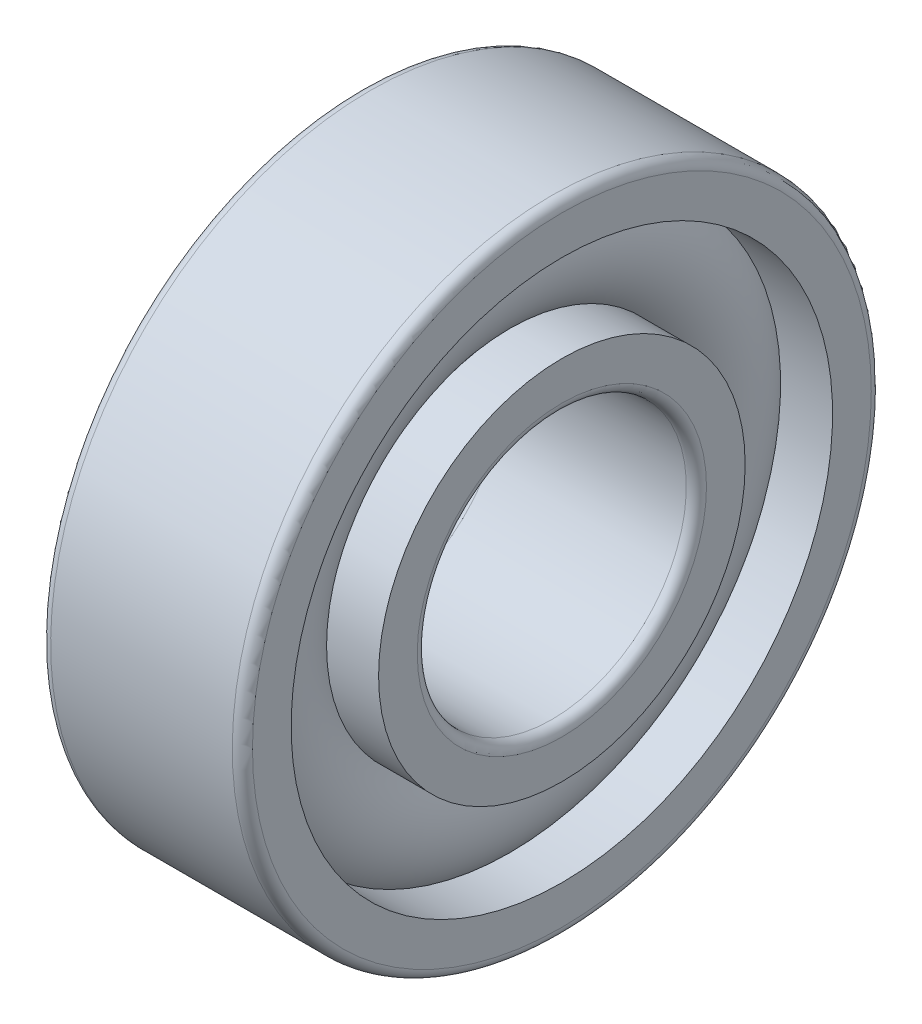
SolidWorks part; units mm, degrees
ref_plane "Plan de face" through (0, 0, 0) normal (0, 0, 1) x (1, 0, 0)
ref_plane "Plan de dessus" through (0, 0, 0) normal (0, 1, 0) x (1, 0, 0)
ref_plane "Plan de droite" through (0, 0, 0) normal (1, 0, 0) x (0, 0, -1)
ref_plane "Plan1" through (0, 0, -411.4604) normal (0, 0, 1) x (1, 0, 0)
sketch "Esquisse1" plane through (0, 0, -411.4604) normal (0, 0, 1) x (1, 0, 0)
  line L0 (-2.7, 4) -> (2.7, 4)
  line L1 (3, 4.3) -> (3, 5.45)
  line L2 (3, 5.45) -> (1.4534, 5.45)
  line L3 (1.4534, 8.05) -> (3, 8.05)
  line L4 (3, 8.05) -> (3, 9.2)
  line L5 (2.7, 9.5) -> (-2.7, 9.5)
  line L6 (-3, 9.2) -> (-3, 8.05)
  line L7 (-3, 8.05) -> (-1.4534, 8.05)
  line L8 (-1.4534, 5.45) -> (-3, 5.45)
  line L9 (-3, 5.45) -> (-3, 4.3)
  line L10 (-3, 0) -> (3, 0) construction
  line L11 (0, 6.75) -> (3, 6.75) construction
  arc A0 (-3, 4.3) -> (-2.7, 4) centre (-2.7, 4.3) ccw
  arc A1 (2.7, 4) -> (3, 4.3) centre (2.7, 4.3) ccw
  arc A2 (1.4534, 5.45) -> (1.4534, 8.05) centre (0, 6.75) ccw
  arc A3 (3, 9.2) -> (2.7, 9.5) centre (2.7, 9.2) ccw
  arc A4 (-2.7, 9.5) -> (-3, 9.2) centre (-2.7, 9.2) ccw
  arc A5 (-1.4534, 8.05) -> (-1.4534, 5.45) centre (0, 6.75) ccw
  point P29 (0, 0)
  dimension "D2" = 0.3
  dimension "D6" = 1.95
  dimension "D1" = 4
  dimension "D3" = 9.5
  dimension "D4" = 2.6
  dimension "D5" = 6
revolve "Révolution1" add sketch "Esquisse1" angle 360 about L10
